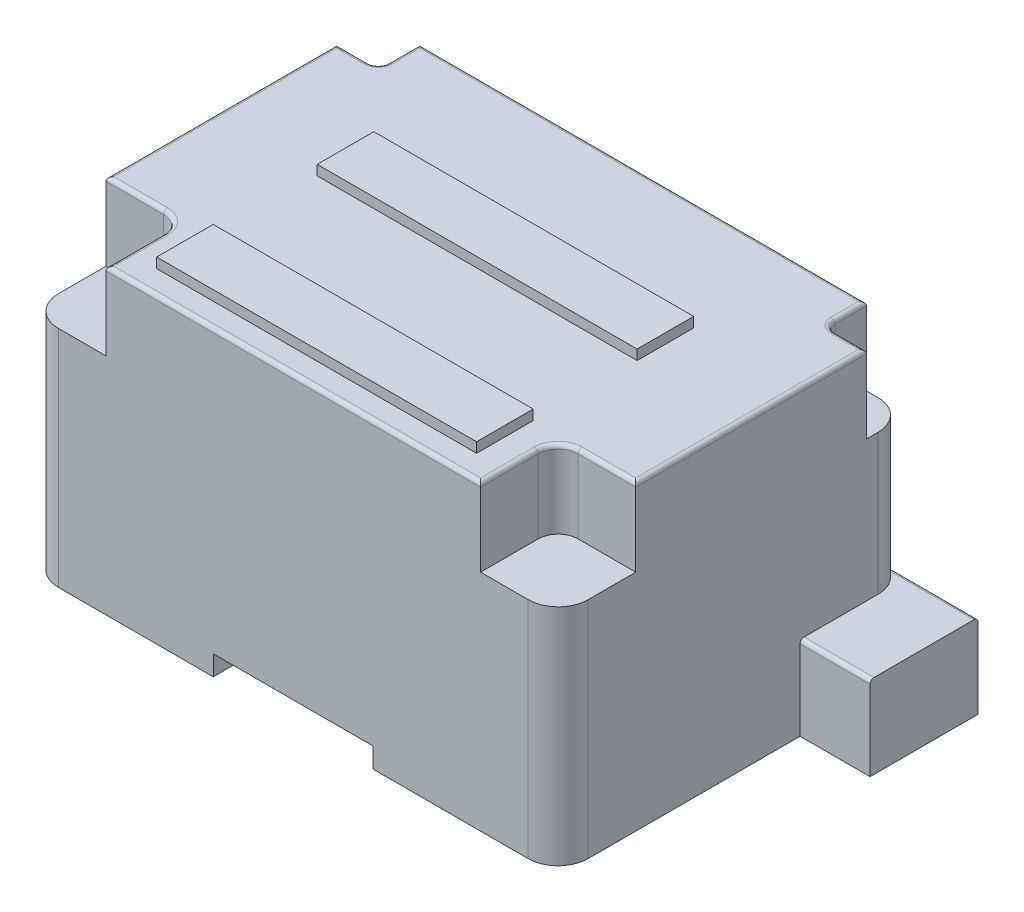
SolidWorks part; units mm, degrees
ref_plane "前视基准面" through (0, 0, 0) normal (0, 0, 1) x (1, 0, 0)
ref_plane "上视基准面" through (0, 0, 0) normal (0, 1, 0) x (1, 0, 0)
ref_plane "右视基准面" through (0, 0, 0) normal (1, 0, 0) x (0, 0, -1)
other "Configuration Table"
sketch "草图1" plane through (0, 0, 0) normal (0, 1, 0) x (1, 0, 0)
  line L1 (-13.25, 8.75) -> (13.25, 8.75)
  line L2 (-13.25, 8.75) -> (-13.25, -8.75)
  line L3 (-13.25, -8.75) -> (13.25, -8.75)
  line L4 (13.25, 8.75) -> (13.25, -8.75)
  line L5 (-13.25, 8.75) -> (13.25, -8.75) construction
  line L6 (-13.25, -8.75) -> (13.25, 8.75) construction
  point P0 (0, 0)
  dimension "D1" = 26.5
  dimension "D2" = 17.5
extrude "凸台-拉伸1" add sketch "草图1" along normal blind 15.1
sketch "草图2" plane through (13.25, 0, 0) normal (1, 0, 0) x (0, 0, -1)
  line L1 (8.75, 0) -> (3.35, 0)
  line L2 (8.75, 0) -> (8.75, 4.2)
  line L3 (8.75, 4.2) -> (3.35, 4.2)
  line L4 (3.35, 0) -> (3.35, 4.2)
  dimension "D1" = 5.4
  dimension "D2" = 4.2
extrude "凸台-拉伸2" add sketch "草图2" along normal blind 3.5
sketch "草图3" plane through (0, 15.1, 0) normal (0, 1, 0) x (1, 0, 0)
  line L1 (-13.25, 8.75) -> (-11.17, 8.75)
  line L2 (-13.25, 8.75) -> (-13.25, 6.67)
  line L3 (-13.25, 6.67) -> (-11.17, 6.67)
  line L4 (-11.17, 8.75) -> (-11.17, 6.67)
  line L5 (-13.25, -8.75) -> (-9.37, -8.75)
  line L6 (-13.25, -8.75) -> (-13.25, -4.87)
  line L7 (-13.25, -4.87) -> (-9.37, -4.87)
  line L8 (-9.37, -8.75) -> (-9.37, -4.87)
  line L9 (13.25, -8.75) -> (9.37, -8.75)
  line L10 (13.25, -8.75) -> (13.25, -4.87)
  line L11 (13.25, -4.87) -> (9.37, -4.87)
  line L12 (9.37, -8.75) -> (9.37, -4.87)
  line L13 (13.25, 8.75) -> (11.17, 8.75)
  line L14 (13.25, 8.75) -> (13.25, 6.67)
  line L15 (13.25, 6.67) -> (11.17, 6.67)
  line L16 (11.17, 8.75) -> (11.17, 6.67)
  point P22 (0, 0)
  dimension "D1" = 2.08
  dimension "D2" = 3.88
  dimension "D3" = 2.08
  dimension "D4" = 2.08
  dimension "D5" = 2.08
  dimension "D6" = 3.88
  dimension "D7" = 3.88
  dimension "D8" = 3.88
extrude "切除-拉伸1" cut sketch "草图3" against normal blind 3.88
sketch "草图4" plane through (0, 0, 0) normal (0, -1, 0) x (1, 0, 0)
  line L0 (-13.25, 8.75) -> (13.25, 8.75) construction
  line L1 (-4, 9.75) -> (4, 9.75)
  line L2 (-4, 9.75) -> (-4, 7.75)
  line L3 (-4, 7.75) -> (4, 7.75)
  line L4 (4, 9.75) -> (4, 7.75)
  line L5 (-4, 9.75) -> (4, 7.75) construction
  line L6 (-4, 7.75) -> (4, 9.75) construction
  point P0 (0, 8.75)
  dimension "D1" = 1
  dimension "D2" = 8
extrude "切除-拉伸2" cut sketch "草图4" against normal blind 1
fillet "圆角1" radius 1.5 4 edges at (-13.25, 5.61, -8.75) (13.25, 7.71, -8.75) (13.25, 5.61, 8.75) (-13.25, 5.61, 8.75)
fillet "圆角2" radius 1 2 edges at (9.37, 13.16, 4.87) (-9.37, 13.16, 4.87)
fillet "圆角3" radius 0.5 2 edges at (-11.17, 13.16, -6.67) (11.17, 13.16, -6.67)
fillet "圆角4" radius 0.2 18 edges at (14.25, 4.2, -8.75) (15, 4.2, -3.35) (13.25, 15.1, -0.9) (11.81, 15.1, 4.87) (9.6629, 15.1, 5.1629) (9.37, 15.1, 7.31) (0, 15.1, 8.75) (-9.37, 15.1, 7.31) (-9.6629, 15.1, 5.1629) (-11.81, 15.1, 4.87) (-13.25, 15.1, -0.9) (-12.46, 15.1, -6.67) (-11.3164, 15.1, -6.8164) (-11.17, 15.1, -7.96) (0, 15.1, -8.75) (11.17, 15.1, -7.96) (11.3164, 15.1, -6.8164) (12.46, 15.1, -6.67)
sketch "草图5" plane through (0, 15.1, 0) normal (0, 1, 0) x (1, 0, 0)
  line L0 (11.17, 8.75) -> (-11.17, 8.75) construction
  line L9 (8, 3.28) -> (-8, 3.28)
  line L10 (8, 3.28) -> (8, 0.45)
  line L11 (8, 0.45) -> (-8, 0.45)
  line L12 (-8, 3.28) -> (-8, 0.45)
  line L13 (8, 3.28) -> (-8, 0.45) construction
  line L14 (8, 0.45) -> (-8, 3.28) construction
  line L15 (8, -4.75) -> (-8, -4.75)
  line L16 (8, -4.75) -> (8, -7.58)
  line L17 (8, -7.58) -> (-8, -7.58)
  line L18 (-8, -4.75) -> (-8, -7.58)
  line L19 (8, -4.75) -> (-8, -7.58) construction
  line L20 (8, -7.58) -> (-8, -4.75) construction
  line L21 (-9.37, -8.75) -> (9.37, -8.75) construction
  point P0 (0, 1.865)
  point P5 (0, -6.165)
  point P10 (0, 0)
  point P12 (0, 0)
  dimension "D1" = 16
  dimension "D2" = 16
  dimension "D3" = 2.83
  dimension "D4" = 8.3
  dimension "D5" = 4
  dimension "D6" = 2.83
extrude "凸台-拉伸3" add sketch "草图5" along normal blind 0.5
